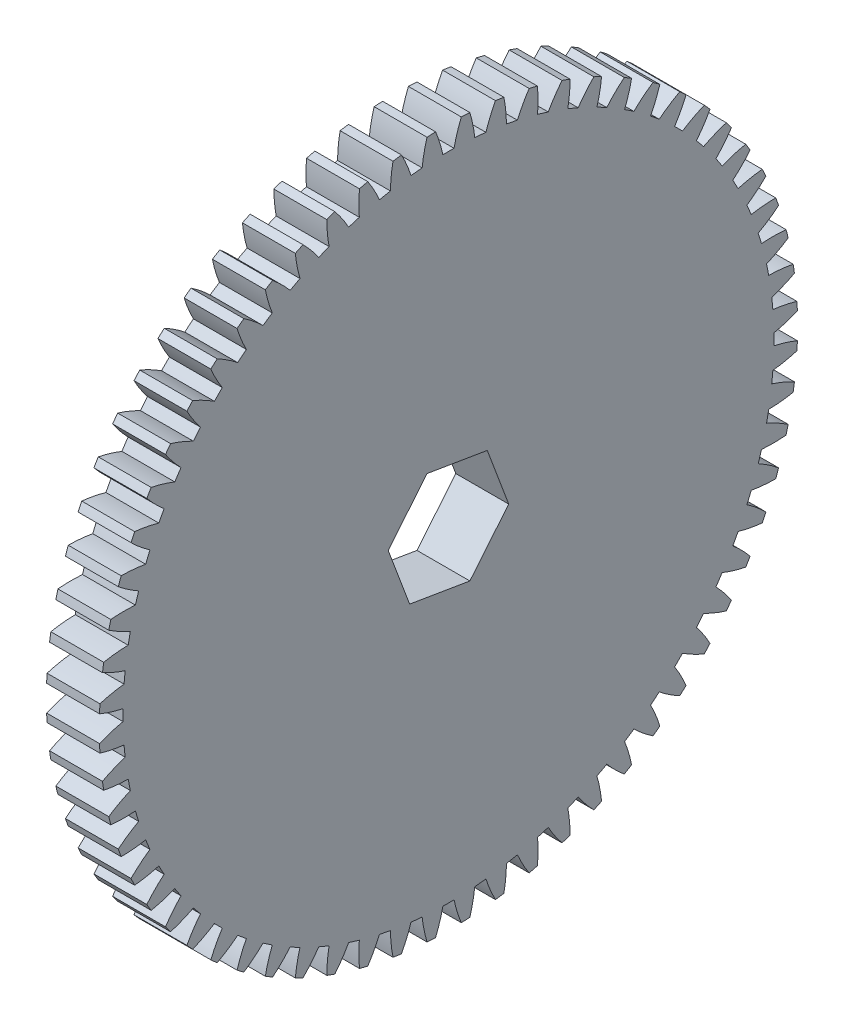
SolidWorks part; units mm, degrees
ref_plane "Plane1" through (0, 0, 0) normal (0, 0, 1) x (1, 0, 0)
ref_plane "Plane2" through (0, 0, 0) normal (0, 1, 0) x (1, 0, 0)
ref_plane "Plane3" through (0, 0, 0) normal (1, 0, 0) x (0, 0, -1)
other "Configuration Table"
sketch "HoldingSke" plane through (0, 0, 0) normal (0, 1, 0) x (1, 0, 0)
  line L0 (0, 0) -> (222.6925, -456.5874)
  line L1 (-15, 0) -> (100, 0) construction
  line L2 (0, 0) -> (-2.1039, 2.3779)
  line L3 (0, 0) -> (-11.863, 4.5341)
  line L4 (0, 0) -> (3.7858, 7.762)
  line L5 (0, 0) -> (-47.5972, -17.7524)
  line L6 (0, 0) -> (-5.2639, -3.5516)
  line L7 (-2.1039, 2.3779) -> (8.8308, 51.9871)
  line L8 (-76.2, 54.61) -> (-61.976, 54.61)
  line L9 (-67.7845, 28.3722) -> (-49.3413, 33.142)
  line L10 (-76.2, 71.12) -> (104.1128, 71.12)
  line L11 (0, 0) -> (-6.35, 0)
  line L12 (-76.2, 101.6) -> (-76.1492, 101.6)
  line L13 (24.9733, 27.94) -> (52.9518, 28.4284)
  line L14 (24.9733, 27.94) -> (25.0241, 27.9398)
  line L15 (24.9733, 27.94) -> (100.4021, 29.52)
  circle A0 centre (0, 0) radius 6.35
  circle A1 centre (0, 0) radius 1.27
  circle A2 centre (0, 0) radius 1.27
  circle A3 centre (0, 0) radius 6.35
  dimension "MHD" = 2.54
  dimension "Hub_dia" = 2.54
  dimension "Bore" = 12.7
  dimension "MBD" = 12.7
  dimension "Num_teeth" = 64
  dimension "Pitch" = 508
  dimension "Overall_len" = 50.8
  dimension "Show_teeth" = 64
  dimension "Thickness" = 6.35
  dimension "OAL" = 50.8001
  dimension "T_dim" = 14.224
  dimension "Ap" = 14.5
  dimension "H" = 19.05
  dimension "Pitch_radius" = 180.3128
  dimension "Width" = 6.35
  dimension "Backlash" = 0.0508
  dimension "Addendum_fac" = 1
  dimension "Dedendum_fac" = 1.2
  dimension "Clearance_fac" = 0.2
  dimension "Dedendum_add" = 0.0508
sketch "BasProSke" plane through (0, 0, 0) normal (0, 1, 0) x (1, 0, 0)
  line L0 (-10, 0) -> (60, 0) construction
  line L1 (0, 0) -> (0, 41.91)
  line L2 (0, 0) -> (6.35, 0)
  line L3 (6.35, 0) -> (6.35, 41.91)
  line L4 (6.35, 41.91) -> (0, 41.91)
  dimension "Thickness" = 6.35
  dimension "Diameter" = 83.82
revolve "Base-Revolve" add sketch "BasProSke" angle 360 about L0
sketch "TooCutSke" plane through (0, 0, 0) normal (1, 0, 0) x (0, 0, -1)
  line L1 (0, 0) -> (0, 107) construction
  line L2 (0, 0) -> (-1.0863, 40.6255) construction
  line L3 (0, 0) -> (-3.9872, 81.1618) construction
  line L4 (-1.0863, 40.6255) -> (-1.9936, 40.5809) construction
  arc A0 (0.6714, 39.0594) -> (-0.6714, 39.0594) centre (0, 0) ccw
  arc A1 (1.555, 41.9066) -> (-1.555, 41.9066) centre (0, 0) ccw
  circle A2 centre (0, 0) radius 40.64 construction
  circle A3 centre (0, 0) radius 39.3455 construction
  arc A4 (-0.6714, 39.0594) -> (-1.555, 41.9066) centre (-16.5732, 35.6847) ccw
  arc A5 (1.555, 41.9066) -> (0.6714, 39.0594) centre (16.5732, 35.6847) ccw
  dimension "Root_dia" = 78.1304
  dimension "Overcut_dia" = 83.8708
  dimension "Pitch_dia" = 81.28
  dimension "Base_dia" = 78.691
  dimension "Flank_rad" = 16.256
  dimension "Half_ang" = 2.813
  dimension "Half_CT" = 0.9085
extrude "ToothCut" cut sketch "TooCutSke" along normal through all
fillet "Breaks" [suppressed] radius 0.0254
fillet "RootFillets" [suppressed] radius 0.3048
pattern_circular "TeethCuts" count 64 every 5.625 about axis through (-10, 0, 0) along (1, 0, 0) of "ToothCut", "RootFillets", "Breaks"
sketch "HubNeaOneSke" plane through (0, 0, 0) normal (-1, 0, 0) x (0, 0, 1)
  circle A0 centre (0, 0) radius 1.27
  dimension "Diameter" = 2.54
extrude "HubNearOne" [suppressed] add sketch "HubNeaOneSke" along normal blind 44.4501
sketch "HubNeaBotSke" plane through (0, 0, 0) normal (-1, 0, 0) x (0, 0, 1)
  circle A0 centre (0, 0) radius 1.27
  dimension "Diameter" = 2.54
extrude "HubNearBoth" add sketch "HubNeaBotSke" along normal blind 22.225
ref_plane "FarPln" through (6.35, 0, 0) normal (1, 0, 0) x (0, 0, -1)
sketch "HubFarSke" plane through (6.35, 0, 0) normal (1, 0, 0) x (0, 0, -1)
  circle A0 centre (0, 0) radius 1.27
  dimension "Diameter" = 2.54
extrude "HubFar" add sketch "HubFarSke" along normal blind 22.225
sketch "BorSke" plane through (0, 0, 0) normal (1, 0, 0) x (0, 0, -1)
  circle A0 centre (0, 0) radius 6.35
  dimension "Diameter" = 12.7
extrude "Bore" cut sketch "BorSke" along normal mid plane 101.6001
sketch "KeySke" plane through (0, 0, 0) normal (1, 0, 0) x (0, 0, -1)
  line L0 (-1.5875, 0) -> (-1.5875, 7.874)
  line L1 (-1.5875, 7.874) -> (1.5875, 7.874)
  line L2 (1.5875, 7.874) -> (1.5875, 0)
  line L3 (0, 0) -> (0, 34) construction
  line L4 (-1.5875, 0) -> (1.5875, 0)
  dimension "Offset" = 7.874
  dimension "Width" = 3.175
extrude "Keyway" [suppressed] cut sketch "KeySke" along normal mid plane 101.6001
pattern_circular "Keyway2" [suppressed] count 2 every 90 about axis through (-10, 0, 0) along (1, 0, 0)
sketch "Sketch1" plane through (6.35, 0, 0) normal (1, 0, 0) x (0, 0, -1)
  line L1 (4.6612, 5.6601) -> (-2.5711, 6.8668)
  line L2 (-2.5711, 6.8668) -> (-7.2324, 1.2067)
  line L3 (-7.2324, 1.2067) -> (-4.6612, -5.6601)
  line L4 (-4.6612, -5.6601) -> (2.5711, -6.8668)
  line L5 (2.5711, -6.8668) -> (7.2324, -1.2067)
  line L6 (7.2324, -1.2067) -> (4.6612, 5.6601)
  circle A0 centre (0, 0) radius 6.35 construction
  dimension "D1" = 12.7
extrude "Cut-Extrude1" cut sketch "Sketch1" against normal through all
equation "' \"Pitch@HoldingSke\" = 4"
equation "' \"Num_teeth@HoldingSke\" = 12"
equation "' \"Ap@HoldingSke\" =  20"
equation "' \"Ap@HoldingSke\" = 20"
equation "' \"Width@HoldingSke\" = 0.5"
equation "' \"Hub_dia@HoldingSke\"= 1"
equation "' \"Hub_dia@HoldingSke\" = 1"
equation "' \"Overall_len@HoldingSke\" = 1.0"
equation "' \"Bore@HoldingSke\" = 0.75"
equation "' \"T_dim@HoldingSke\" = 0.85"
equation "' \"Width@KeySke\" = 0.25"
equation "' \"Show_teeth@HoldingSke\" = 13"
equation "' \"Backlash@HoldingSke\" = 0.009"
equation "' \"Addendum_fac@HoldingSke\" = 1.0"
equation "' \"Dedendum_fac@HoldingSke\" = 1.25"
equation "' \"Dedendum_add@HoldingSke\" = 0.00005"
equation "' \"Clearance_fac@HoldingSke\" = 0.25"
equation "' \"Pitch@HoldingSke\" = 0.5"
equation "' \"Num_teeth@HoldingSke\" = 23"
equation "' \"Show_teeth@HoldingSke\" = 23"
equation "' \"Backlash@HoldingSke\" = 0.0375"
equation "\"Overcut_dia@TooCutSke\" = (\"Num_teeth@HoldingSke\" + 2 * \"Addendum_fac@HoldingSke\") / \"Pitch@HoldingSke\" + 0.002"
equation "\"Pitch_dia@TooCutSke\" = \"Num_teeth@HoldingSke\" / \"Pitch@HoldingSke\""
equation "\"Base_dia@TooCutSke\" = \"Num_teeth@HoldingSke\" / \"Pitch@HoldingSke\" * cos((\"Ap@HoldingSke\"  * 3.14159265 / 180))"
equation "\"Root_dia@TooCutSke\" = (\"Num_teeth@HoldingSke\" + 2) / \"Pitch@HoldingSke\" - 2 * (\"Addendum_fac@HoldingSke\" + \"Dedendum_fac@HoldingSke\") / \"Pitch@HoldingSke\" - \"Dedendum_add@HoldingSke\" * 2"
equation "\"Half_ang@TooCutSke\" = 180 / \"Num_teeth@HoldingSke\""
equation "\"Half_CT@TooCutSke\" = \"Num_teeth@HoldingSke\" / \"Pitch@HoldingSke\" * sin((3.14159265 / 2 / \"Num_teeth@HoldingSke\")) / 2 - 7 * \"Backlash@HoldingSke\" / 4"
equation "\"Flank_rad@TooCutSke\" = \"Num_teeth@HoldingSke\" / \"Pitch@HoldingSke\" / 5"
equation "\"Radius@RootFillets\" = \"Clearance_fac@HoldingSke\" / \"Pitch@HoldingSke\" + \"Dedendum_add@HoldingSke\""
equation "\"Break_rad@Breaks\" = 0.02 / \"Pitch@HoldingSke\""
equation "\"Thickness@HoldingSke\" = \"Width@HoldingSke\""
equation "\"OAL@HoldingSke\" = \"Thickness@HoldingSke\""
equation "\"MHD@HoldingSke\" = (\"Num_teeth@HoldingSke\" + 2) / \"Pitch@HoldingSke\" - 2 * (\"Addendum_fac@HoldingSke\" + \"Dedendum_fac@HoldingSke\")  / \"Pitch@HoldingSke\" - \"Dedendum_add@HoldingSke\" * 2"
equation "\"MBD@HoldingSke\" = (\"Num_teeth@HoldingSke\" + 2) / \"Pitch@HoldingSke\" - 2 * (\"Addendum_fac@HoldingSke\" + \"Dedendum_fac@HoldingSke\")  / \"Pitch@HoldingSke\" - \"Dedendum_add@HoldingSke\" * 2 - 0.002"
equation "\"MHD@HoldingSke\" = ((sgn( \"MHD@HoldingSke\" - \"Hub_dia@HoldingSke\" )-1)*( \"MHD@HoldingSke\" - \"Hub_dia@HoldingSke\" ))/-2+ \"Hub_dia@HoldingSke\""
equation "\"MBD@HoldingSke\" = ((sgn( \"MBD@HoldingSke\" - \"Bore@HoldingSke\" )-1)*( \"MBD@HoldingSke\" - \"Bore@HoldingSke\" ))/-2+ \"Bore@HoldingSke\""
equation "\"OAL@HoldingSke\" = ((sgn( \"OAL@HoldingSke\" - \"Overall_len@HoldingSke\" )+1)*( \"OAL@HoldingSke\" - \"Overall_len@HoldingSke\" ))/2 + \"Overall_len@HoldingSke\" + 0.000002"
equation "\"Num_teeth@TeethCuts\" = int( \"Show_teeth@HoldingSke\" ) + 1"
equation "\"Num_teeth@TeethCuts\" = ((sgn( \"Num_teeth@TeethCuts\" - \"Num_teeth@HoldingSke\" )-1)*( \"Num_teeth@TeethCuts\" - \"Num_teeth@HoldingSke\" ))/-2+ \"Num_teeth@HoldingSke\""
equation "\"Num_teeth@TeethCuts\" = ((sgn( \"Num_teeth@TeethCuts\" - 2.0)+1)*( \"Num_teeth@TeethCuts\" - 2.0))/2 +2.0"
equation "\"Angle@TeethCuts\" = 360.0 / \"Num_teeth@HoldingSke\""
equation "\"Diameter@BasProSke\" = (\"Num_teeth@HoldingSke\" + 2 * \"Addendum_fac@HoldingSke\") / \"Pitch@HoldingSke\""
equation "\"Thickness@BasProSke\"  = \"Thickness@HoldingSke\""
equation "' \"Fillet_rad@BasProSke\" =  \"Thickness@HoldingSke\" * 0.05"
equation "' \"Fillet_rad@BasProSke\" = \"Thickness@HoldingSke\" * 0.05"
equation "\"MHD@HoldingSke\" = ((sgn( \"MHD@HoldingSke\" - \"Root_dia@TooCutSke\" )-1)*( \"MHD@HoldingSke\" - \"Root_dia@TooCutSke\" ))/-2+ \"Root_dia@TooCutSke\""
equation "\"Diameter@HubNeaOneSke\" = \"MHD@HoldingSke\""
equation "\"Length@HubNearOne\" = \"OAL@HoldingSke\" - \"Thickness@BasProSke\""
equation "\"Diameter@HubNeaBotSke\" = \"MHD@HoldingSke\""
equation "\"Length@HubNearBoth\" = ( \"OAL@HoldingSke\" - \"Thickness@BasProSke\" ) / 2.0"
equation "\"Thickness@FarPln\" = \"Thickness@BasProSke\""
equation "\"Diameter@HubFarSke\" = \"MHD@HoldingSke\""
equation "\"Length@HubFar\" = ( \"OAL@HoldingSke\" - \"Thickness@BasProSke\" ) / 2.0"
equation "\"Diameter@BorSke\" = \"MBD@HoldingSke\""
equation "\"D1@Bore\" = \"OAL@HoldingSke\" * 2.0"
equation "\"D1@Keyway\" = \"OAL@HoldingSke\" * 2.0"
equation "\"Offset@KeySke\" = \"T_dim@HoldingSke\" - \"MBD@HoldingSke\" / 2.0"
